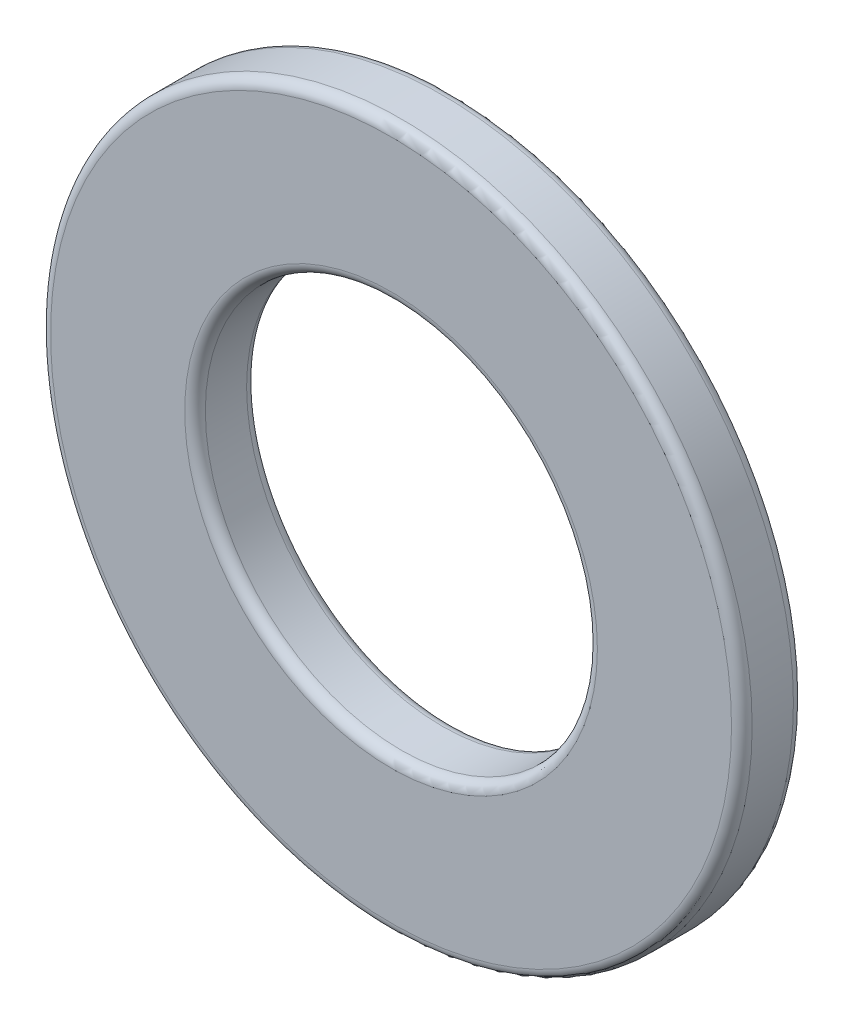
SolidWorks part; units mm, degrees
ref_plane "Front Plane" through (0, 0, 0) normal (0, 0, 1) x (1, 0, 0)
ref_plane "Top Plane" through (0, 0, 0) normal (0, 1, 0) x (1, 0, 0)
ref_plane "Right Plane" through (0, 0, 0) normal (1, 0, 0) x (0, 0, -1)
sketch "Sketch1" plane through (0, 0, 0) normal (0, 0, 1) x (1, 0, 0)
  circle A0 centre (0, 0) radius 9.5
  circle A1 centre (0, 0) radius 17
  dimension "D1" = 19
  dimension "D2" = 34
extrude "Boss-Extrude1" add sketch "Sketch1" along normal blind 3
fillet "Fillet1" radius 0.5 4 edges at (9.5, 0, 0) (17, 0, 0) (17, 0, 3) (9.5, 0, 3)
